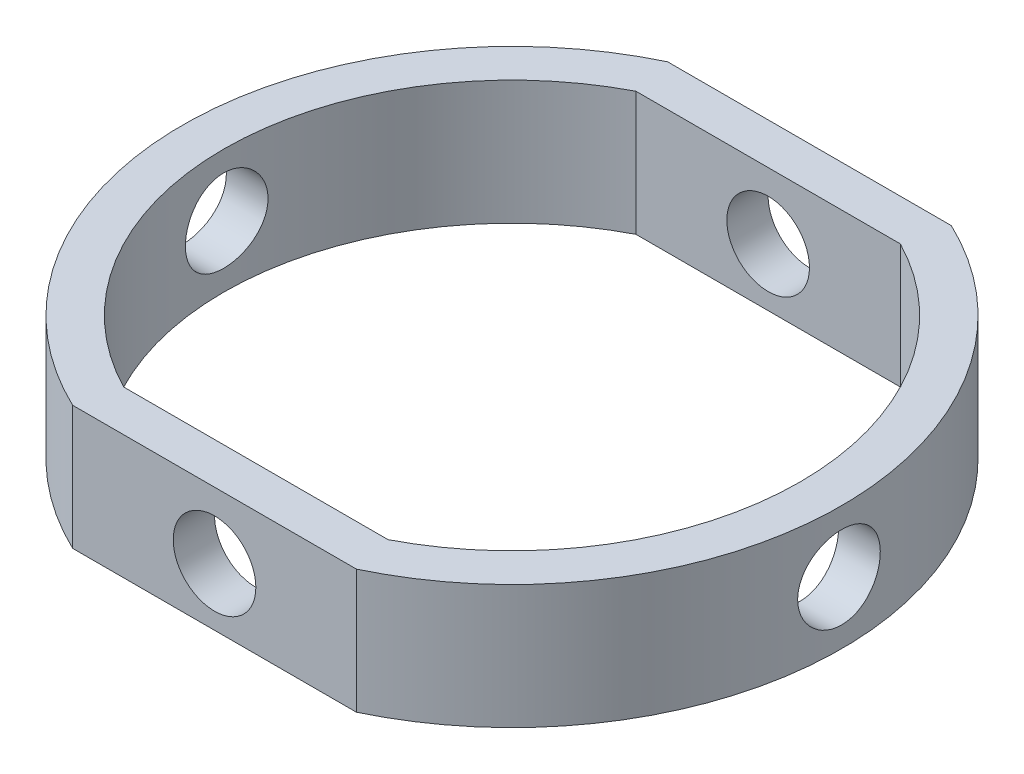
SolidWorks part; units mm, degrees
ref_plane "Front Plane" through (0, 0, 0) normal (0, 0, 1) x (1, 0, 0)
ref_plane "Top Plane" through (0, 0, 0) normal (0, 1, 0) x (1, 0, 0)
ref_plane "Right Plane" through (0, 0, 0) normal (1, 0, 0) x (0, 0, -1)
sketch "Sketch1" plane through (0, 0, 0) normal (0, 1, 0) x (1, 0, 0)
  line L0 (0, 0) -> (0, -25135.2008) construction
  line L1 (0, 0) -> (25135.2008, 0) construction
  line L2 (-16, 31) -> (16, 31)
  line L3 (-16, -31) -> (16, -31)
  line L4 (-17.1714, -36) -> (17.1714, -36)
  line L5 (-17.1714, 36) -> (17.1714, 36)
  arc A0 (16, 31) -> (16, -31) centre (0, 0) cw
  arc A1 (-16, 31) -> (-16, -31) centre (0, 0) ccw
  arc A2 (17.1714, 36) -> (17.1714, -36) centre (0, 0) cw
  arc A3 (-17.1714, 36) -> (-17.1714, -36) centre (0, 0) ccw
  point P6 (0, 31)
  point P10 (0, 31)
  dimension "D2" = 5
  dimension "D1" = 32
  dimension "D3" = 31
extrude "Boss-Extrude1" add sketch "Sketch1" along normal mid plane 15
sketch "Sketch2" plane through (0, 0, 36) normal (0, 0, 1) x (1, 0, 0)
  line L0 (0, 0) -> (0, -50000) construction
  line L2 (-17.1714, 7.5) -> (17.1714, 7.5) construction
  circle A0 centre (0, -0.5) radius 5
  point P6 (0, 0)
  dimension "D1" = 10
  dimension "D2" = 8
extrude "Cut-Extrude1" cut sketch "Sketch2" against normal up to surface (72 mm away) up to face at (0, 0, -36)
ref_plane "Plane1" through (-39.8855, 0, 0) normal (-1, 0, 0) x (0, 0, 1)
sketch "Sketch3" plane through (-39.8855, 0, 0) normal (-1, 0, 0) x (0, 0, 1)
  circle A0 centre (0, 0) radius 5
  dimension "D1" = 10
extrude "Cut-Extrude2" cut sketch "Sketch3" against normal up to surface (79.4564 mm away)
sketch "Sketch4" plane through (0, 0, 0) normal (0, 1, 0) x (1, 0, 0)
  line L0 (0, 0) -> (50000, 0) construction
  arc A1 (-16, 31) -> (-16, -31) centre (0, 0) ccw construction
  arc A2 (16, -31) -> (16, 31) centre (0, 0) ccw construction
  point P3 (-34.8855, 0)
  point P4 (34.8855, 0)
